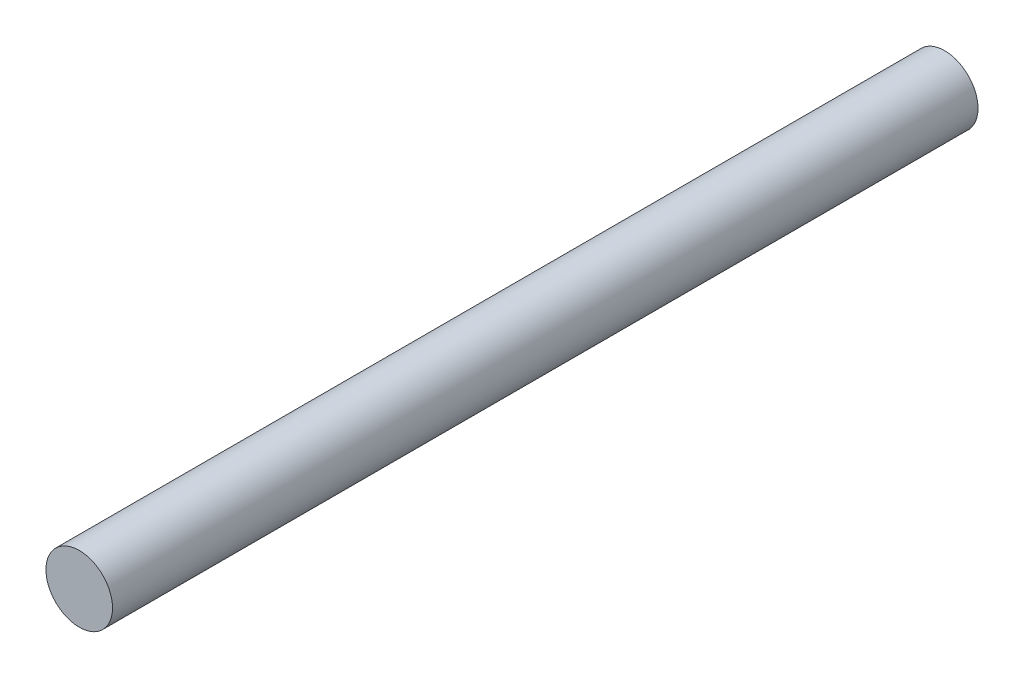
SolidWorks part; units mm, degrees
ref_plane "Front Plane" through (0, 0, 0) normal (0, 0, 1) x (1, 0, 0)
ref_plane "Top Plane" through (0, 0, 0) normal (0, 1, 0) x (1, 0, 0)
ref_plane "Right Plane" through (0, 0, 0) normal (1, 0, 0) x (0, 0, -1)
sketch "Sketch2" plane through (0, 0, 0) normal (0, 0, 1) x (1, 0, 0)
  circle A0 centre (0, 0) radius 5
extrude "Boss-Extrude1" add sketch "Sketch2" along normal blind 130
